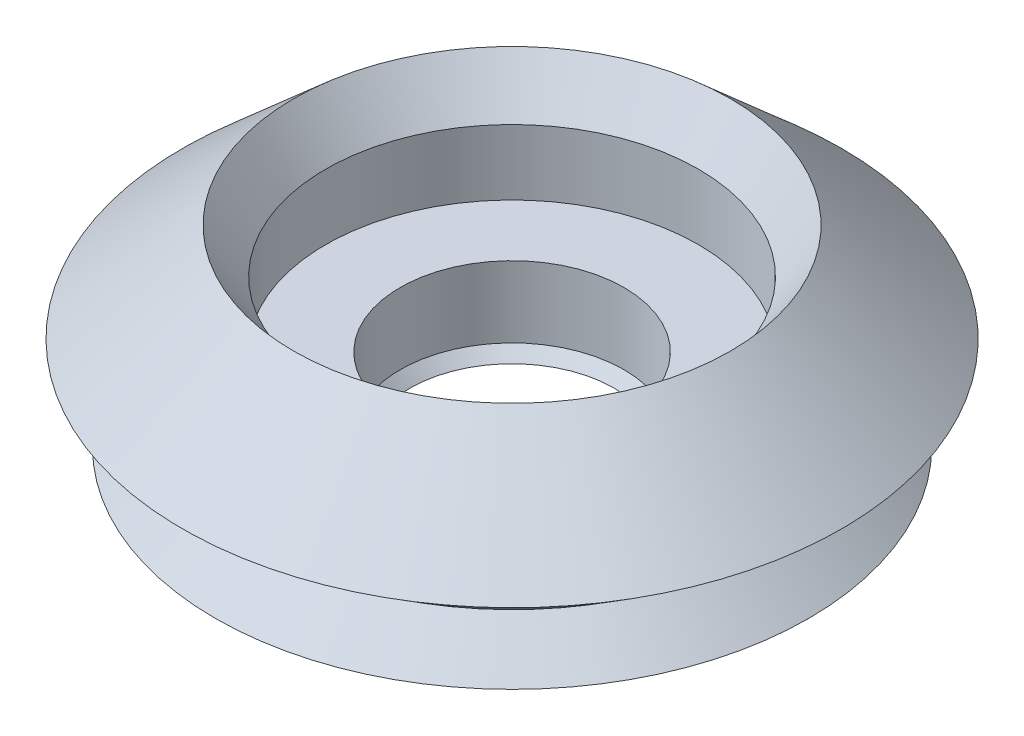
SolidWorks part; units mm, degrees
ref_plane "Front Plane" through (0, 0, 0) normal (0, 0, 1) x (1, 0, 0)
ref_plane "Top Plane" through (0, 0, 0) normal (0, 1, 0) x (1, 0, 0)
ref_plane "Right Plane" through (0, 0, 0) normal (1, 0, 0) x (0, 0, -1)
sketch "Sketch1" plane through (0, 0, 0) normal (0, 0, 1) x (1, 0, 0)
  line L0 (0, 0) -> (0, 37.9419) construction
  line L1 (-20.8472, 0) -> (-20.8472, 13.2588)
  line L2 (-20.8472, 13.2588) -> (-34.6897, 13.2588)
  line L3 (-34.6897, 13.2588) -> (-34.6897, 25.4336)
  line L4 (-34.6897, 25.4336) -> (-40.6937, 33.7724)
  line L5 (-40.6937, 33.7724) -> (-61.3741, 15.4269)
  line L6 (-61.3741, 15.4269) -> (-47.198, 5.0867)
  line L7 (-47.198, 5.0867) -> (-55.2592, -2.0643)
  line L8 (-55.2592, -2.0643) -> (-19.0126, -2.0643)
  line L9 (-19.0126, -2.0643) -> (-20.8472, 0)
revolve "Revolve1" add sketch "Sketch1" angle 360 about L0
